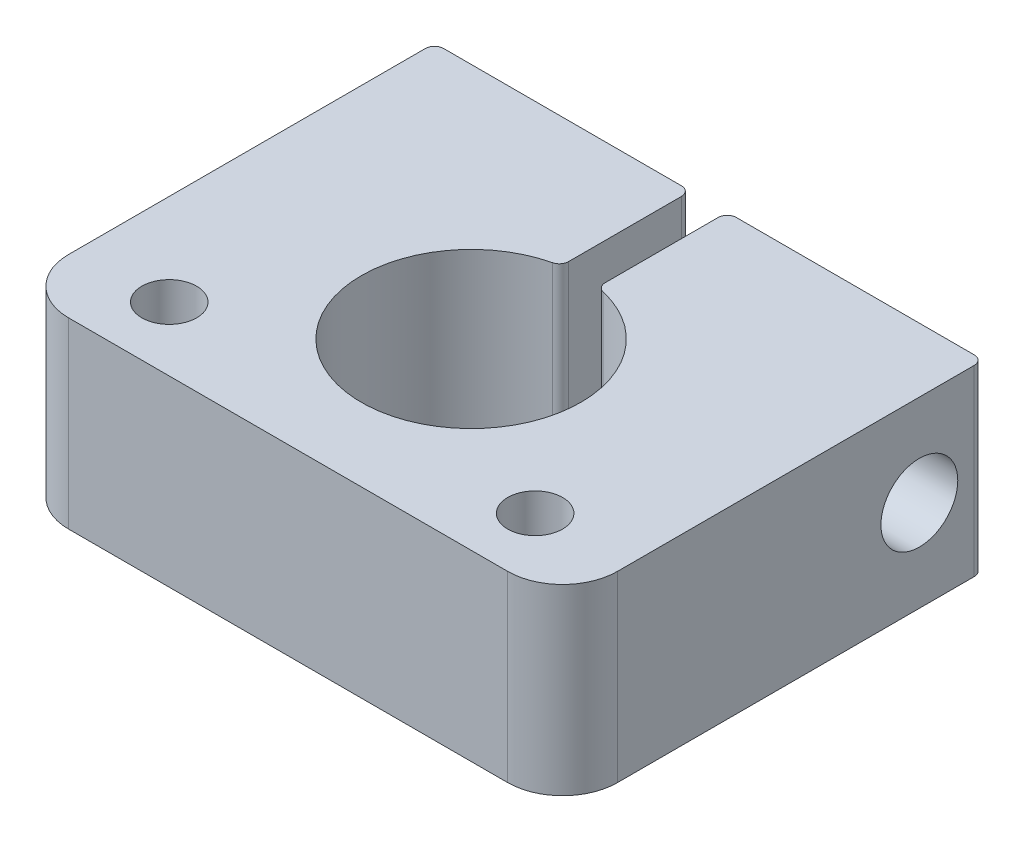
SolidWorks part; units mm, degrees
ref_plane "Front" through (0, 0, 0) normal (0, 0, 1) x (1, 0, 0)
ref_plane "Top" through (0, 0, 0) normal (0, 1, 0) x (1, 0, 0)
ref_plane "Right" through (0, 0, 0) normal (1, 0, 0) x (0, 0, -1)
sketch "Sketch1" plane through (0, 0, 0) normal (0, 1, 0) x (1, 0, 0)
  line L1 (0, 0) -> (30, 0)
  line L2 (0, 0) -> (0, -23)
  line L3 (0, -23) -> (30, -23)
  line L4 (30, 0) -> (30, -23)
  circle A0 centre (15, -13) radius 6
  circle A1 centre (5, -19.5) radius 1.5
  circle A2 centre (25, -19.5) radius 1.5
  dimension "D3" = 12
  dimension "D4" = 3
  dimension "D5" = 3.5
  dimension "D6" = 10
  dimension "D7" = 15
  dimension "D8" = 5
  dimension "D9" = 5
  dimension "D1" = 30
  dimension "D2" = 23
extrude "Boss-Extrude1" add sketch "Sketch1" along normal blind 10
sketch "Sketch2" plane through (0, 10, 0) normal (0, 1, 0) x (1, 0, 0)
  line L0 (15, -7) -> (15, 6.973) construction
  line L1 (30, 0) -> (0, 0) construction
  line L2 (14, 3) -> (16, 3)
  line L3 (14, 3) -> (14, -12)
  line L4 (14, -12) -> (16, -12)
  line L5 (16, 3) -> (16, -12)
  line L6 (14, 3) -> (16, -12) construction
  line L7 (14, -12) -> (16, 3) construction
  circle A0 centre (15, -13) radius 6 construction
  point P5 (15, -4.5)
  dimension "D1" = 2
  dimension "D2" = 15
  dimension "D3" = 3
extrude "Cut-Extrude1" cut sketch "Sketch2" against normal blind 10
sketch "Sketch3" plane through (30, 0, 0) normal (1, 0, 0) x (0, 0, -1)
  line L0 (-23, 10) -> (0, 10) construction
  line L1 (0, 10) -> (0, 0) construction
  circle A0 centre (-3.5, 5) radius 2.1
  dimension "D1" = 5
  dimension "D2" = 3.5
  dimension "D3" = 4.2
extrude "Cut-Extrude2" cut sketch "Sketch3" against normal up to next
sketch "Sketch4" plane through (14, 0, 0) normal (1, 0, 0) x (0, 0, -1)
  circle A0 centre (-3.5, 5) radius 1.25
  dimension "D1" = 2.5
extrude "Cut-Extrude3" cut sketch "Sketch4" against normal blind 20
fillet "Fillet1" radius 3 2 edges at (0, 5, 23) (30, 5, 23)
fillet "Fillet2" radius 0.5 6 edges at (0, 5, 0) (16, 5, 7.0839) (14, 5, 7.0839) (14, 5, 0) (16, 5, 0) (30, 5, 0)
